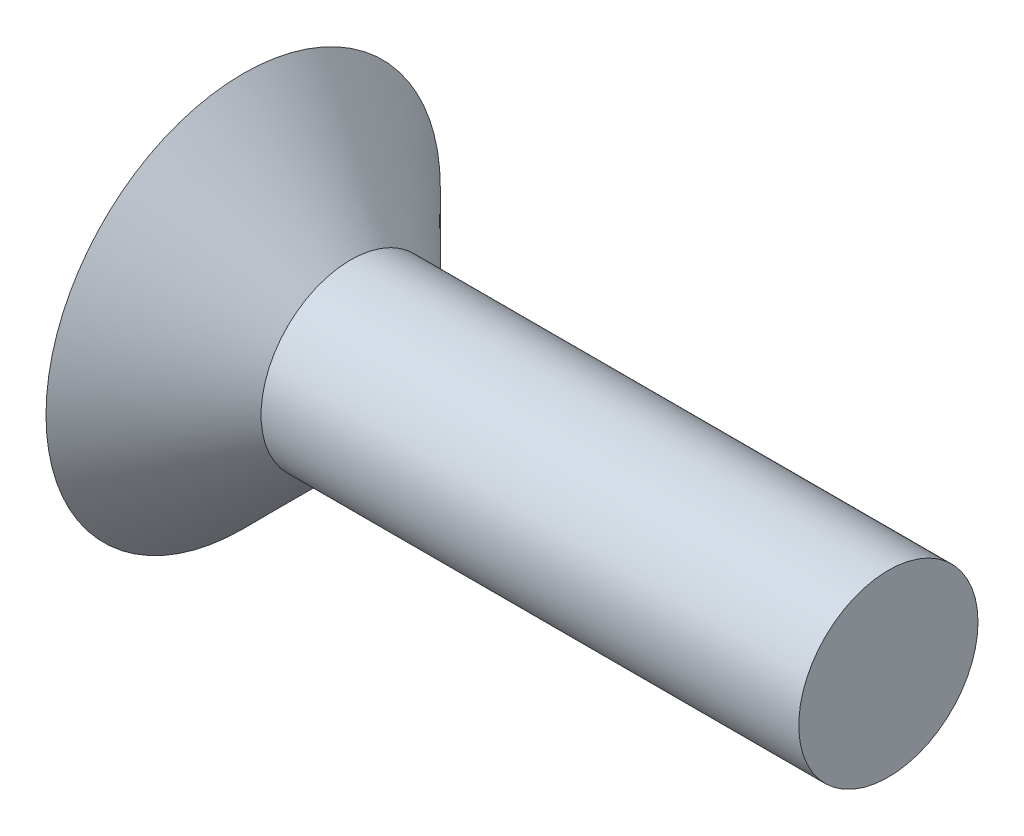
SolidWorks part; units mm, degrees
ref_plane "Спереди" through (0, 0, 0) normal (0, 0, 1) x (1, 0, 0)
ref_plane "Сверху" through (0, 0, 0) normal (0, 1, 0) x (1, 0, 0)
ref_plane "Справа" through (0, 0, 0) normal (1, 0, 0) x (0, 0, -1)
sketch "Эскиз1" plane through (0, 0, 0) normal (0, 0, 1) x (1, 0, 0)
  line L0 (0, 0) -> (0, 2.2)
  line L1 (0, 2.2) -> (1.2, 1)
  line L2 (1.2, 1) -> (7.2, 1)
  line L3 (7.2, 1) -> (7.2, 0)
  line L4 (7.2, 0) -> (0, 0)
  line L5 (0, 0) -> (-2.697, 0) construction
  dimension "D1" = 2
  dimension "D2" = 45
  dimension "D3" = 1.2
  dimension "D4" = 6
revolve "Повернуть1" add sketch "Эскиз1" angle 360 about L5
cosmetic thread "Условное изображение резьбы1" parameters "D2"=2
